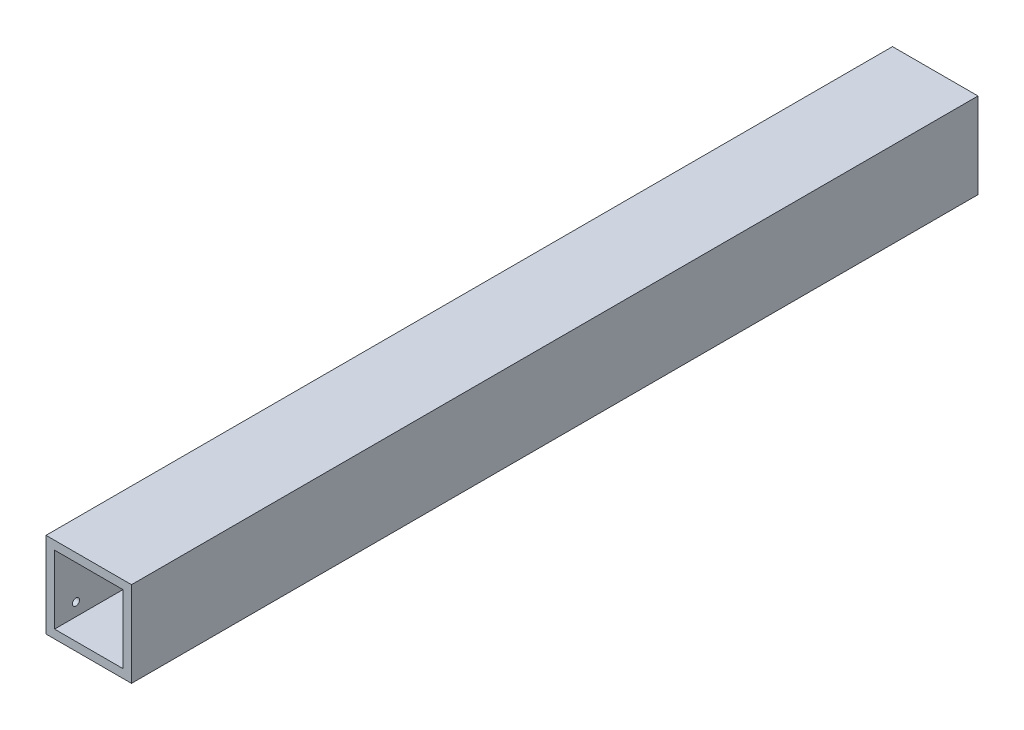
SolidWorks part; units mm, degrees
material "Д16Т ГОСТ 4784-74"
ref_plane "Спереди" through (0, 0, 0) normal (0, 0, 1) x (1, 0, 0)
ref_plane "Сверху" through (0, 0, 0) normal (0, 1, 0) x (1, 0, 0)
ref_plane "Справа" through (0, 0, 0) normal (1, 0, 0) x (0, 0, -1)
sketch "Эскиз1" plane through (0, 0, 0) normal (0, 0, 1) x (1, 0, 0)
  line L1 (0, 0) -> (40, 0)
  line L2 (0, 0) -> (0, 40)
  line L3 (0, 40) -> (40, 40)
  line L4 (40, 0) -> (40, 40)
  dimension "D1" = 40
  dimension "D2" = 40
extrude "Вытянуть-Тонкостенный1" add sketch "Эскиз1" along normal blind 396 thin thin type one direction reverse wall 4
hole_wizard "Отверстие обработанное метчиком M61" positions "Эскиз3" profile "Эскиз2" tap size "M6" standard "DIN"
sketch "Эскиз3" plane through (0, 0, 0) normal (-1, 0, 0) x (0, 0, 1)
  line L0 (396, 0) -> (0, 0) construction
  line L1 (0, 40) -> (0, 0) construction
  line L2 (30, 20) -> (80, 20) construction
  point P0 (30, 20)
  point P8 (80, 20)
  point P9 (130, 20)
  point P10 (180, 20)
  point P11 (230, 20)
  point P12 (280, 20)
  point P13 (330, 20)
  dimension "D1" = 20
  dimension "D2" = 30
  dimension "D4" = 50
  dimension "D3" = 7
sketch "Эскиз2" plane through (0, 20, 30) normal (0, 1, 0) x (0, 0, 1)
  line L0 (0, 0) -> (0, 18.5022)
  line L1 (0, 18.5022) -> (2.5, 17)
  line L2 (2.5, 17) -> (2.5, 0.3031)
  line L3 (2.5, 0.3031) -> (3.025, 0)
  line L5 (3.025, 0) -> (0, 0)
  line L6 (-2.5, 0.3031) -> (-3.025, 0) construction
  line L10 (0, 18.5022) -> (-2.5, 17) construction
  line L11 (0, -6.35) -> (0, 107.95) construction
  dimension "Диаметр сверла" = 5
  dimension "Глубина сверла" = 17
  dimension "Диаметр передней зенковки" = 6.05
  dimension "Угол передней зенковки" = 120
  dimension "Угол заточки сверла" = 118
cosmetic thread "Отверстие резьбы1" parameters "D1"=4, "D2"=6
cosmetic thread "Отверстие резьбы2" parameters "D1"=4, "D2"=6
cosmetic thread "Отверстие резьбы3" parameters "D1"=4, "D2"=6
cosmetic thread "Отверстие резьбы4" parameters "D1"=4, "D2"=6
cosmetic thread "Отверстие резьбы5" parameters "D1"=4, "D2"=6
cosmetic thread "Отверстие резьбы6" parameters "D1"=4, "D2"=6
cosmetic thread "Отверстие резьбы7" parameters "D1"=4, "D2"=6
hole_wizard "Отверстие обработанное метчиком M41" positions "Эскиз5" profile "Эскиз4" tap size "M4" standard "DIN"
sketch "Эскиз5" plane through (0, 0, 0) normal (-1, 0, 0) x (0, 0, 1)
  line L0 (396, 0) -> (0, 0) construction
  line L1 (396, 40) -> (396, 0) construction
  point P0 (386, 10)
  point P11 (366, 10)
  point P12 (386, 30)
  point P13 (366, 30)
  dimension "D1" = 10
  dimension "D2" = 10
  dimension "D3" = 2
  dimension "D4" = 2
sketch "Эскиз4" plane through (0, 10, 386) normal (0, 1, 0) x (0, 0, 1)
  line L0 (0, 0) -> (0, 12.4914)
  line L1 (0, 12.4914) -> (1.65, 11.5)
  line L2 (1.65, 11.5) -> (1.65, 0.2165)
  line L3 (1.65, 0.2165) -> (2.025, 0)
  line L5 (2.025, 0) -> (0, 0)
  line L6 (-1.65, 0.2165) -> (-2.025, 0) construction
  line L10 (0, 12.4914) -> (-1.65, 11.5) construction
  line L11 (0, -6.35) -> (0, 107.95) construction
  dimension "Диаметр сверла" = 3.3
  dimension "Глубина сверла" = 11.5
  dimension "Диаметр передней зенковки" = 4.05
  dimension "Угол передней зенковки" = 120
  dimension "Угол заточки сверла" = 118
cosmetic thread "Отверстие резьбы8" parameters "D1"=4, "D2"=4
cosmetic thread "Отверстие резьбы9" parameters "D1"=4, "D2"=4
cosmetic thread "Отверстие резьбы10" parameters "D1"=4, "D2"=4
cosmetic thread "Отверстие резьбы11" parameters "D1"=4, "D2"=4
